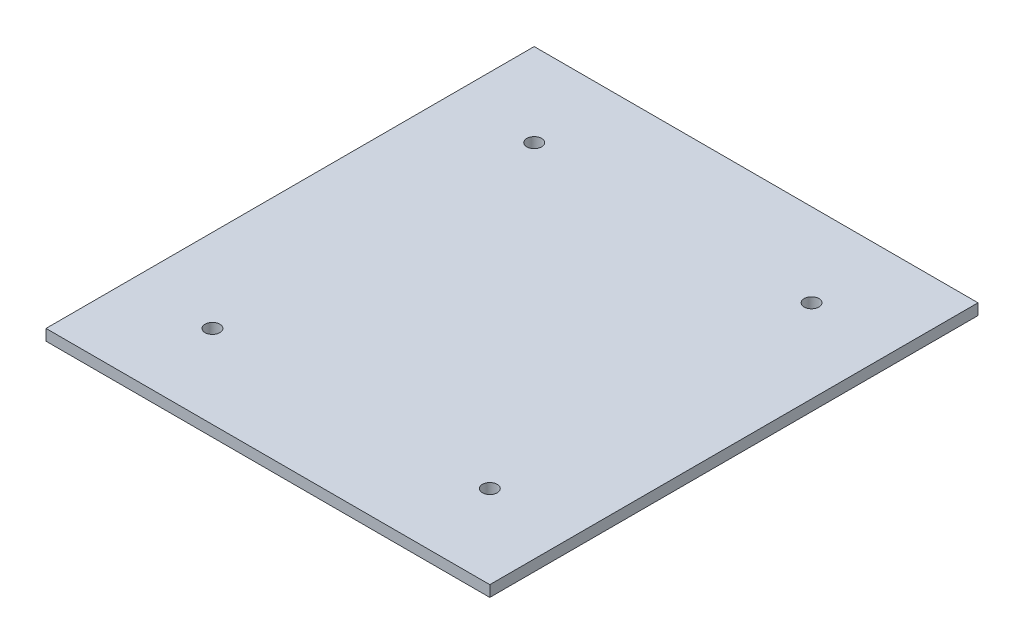
SolidWorks part; units mm, degrees
ref_plane "Front Plane" through (0, 0, 0) normal (0, 0, 1) x (1, 0, 0)
ref_plane "Top Plane" through (0, 0, 0) normal (0, 1, 0) x (1, 0, 0)
ref_plane "Right Plane" through (0, 0, 0) normal (1, 0, 0) x (0, 0, -1)
sketch "Sketch2" plane through (0, 0, 0) normal (0, 1, 0) x (1, 0, 0)
  line L0 (37.5, -43.5) -> (47.5, -43.5)
  line L1 (-47.5, -53.5) -> (47.5, -53.5)
  line L2 (-47.5, -53.5) -> (-47.5, 53.5)
  line L3 (-47.5, 53.5) -> (47.5, 53.5)
  line L4 (47.5, -53.5) -> (47.5, 53.5)
  line L5 (-47.5, -53.5) -> (47.5, 53.5) construction
  line L6 (-47.5, 53.5) -> (47.5, -53.5) construction
  line L7 (37.5, -43.5) -> (37.5, -53.5)
  line L8 (-55, 0) -> (55, 0) construction
  line L9 (0, -55) -> (0, 55) construction
  line L15 (-60, 66) -> (60, 66)
  line L16 (-60, 66) -> (-60, -66)
  line L17 (-60, -66) -> (60, -66)
  line L18 (60, 66) -> (60, -66)
  line L19 (-60, 66) -> (60, -66) construction
  line L20 (-60, -66) -> (60, 66) construction
  circle A1 centre (37.5, -43.5) radius 2
  circle A2 centre (37.5, 43.5) radius 2
  circle A3 centre (-37.5, -43.5) radius 2
  circle A4 centre (-37.5, 43.5) radius 2
  point P0 (0, 0)
  point P20 (0, 0)
  point P21 (0, 0)
  dimension "D3" = 10
  dimension "D5" = 4
  dimension "D1" = 95
  dimension "D2" = 107
  dimension "D4" = 10
  dimension "D6" = 120
  dimension "D7" = 132
extrude "Boss-Extrude1" add sketch "Sketch2" along normal blind 3 contours L18 L15 L16 L17 L4 L1 L2 L3 | A1 L0 L4 L3 L2 L1 L7 A4 A2 A3 | A1 L7 L1 L4 L0
